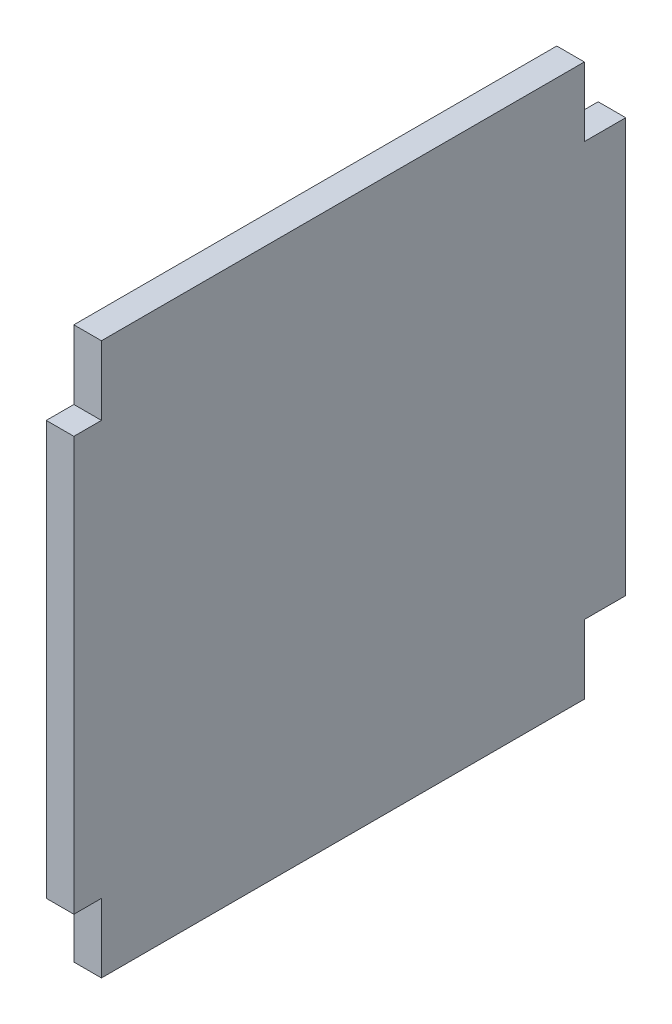
SolidWorks part; units mm, degrees
material "PVC rigido"
ref_plane "Piano frontale" through (0, 0, 0) normal (0, 0, 1) x (1, 0, 0)
ref_plane "Piano superiore" through (0, 0, 0) normal (0, 1, 0) x (1, 0, 0)
ref_plane "Piano destro" through (0, 0, 0) normal (1, 0, 0) x (0, 0, -1)
sketch "Schizzo1" plane through (0, 0, 0) normal (0, 0, 1) x (1, 0, 0)
  line L1 (214, 15) -> (216, 15)
  line L2 (214, 15) -> (214, -15)
  line L3 (214, -15) -> (216, -15)
  line L4 (216, 15) -> (216, -15)
extrude "Estrusione-Estrusione1" add sketch "Schizzo1" along normal up to surface (37 mm away) and the other way up to surface (3 mm away)
ref_plane "Piano1" through (0, 0, 0) normal (0, 1, 0) x (1, 0, 0)
sketch "Schizzo2" plane through (0, -15, 0) normal (0, -1, 0) x (1, 0, 0)
  line L0 (214, 37) -> (214, -3) construction
  line L1 (216, 0) -> (214, 0)
  line L2 (216, 0) -> (216, 35)
  line L3 (216, 35) -> (214, 35)
  line L4 (214, 0) -> (214, 35)
  line L5 (216, 35) -> (214, 35) construction
extrude "Estrusione-Estrusione2" add sketch "Schizzo2" along normal blind 5
mirror "Specchia1" about plane through (0, 0, 0) normal (0, 1, 0) of "Estrusione-Estrusione2"
